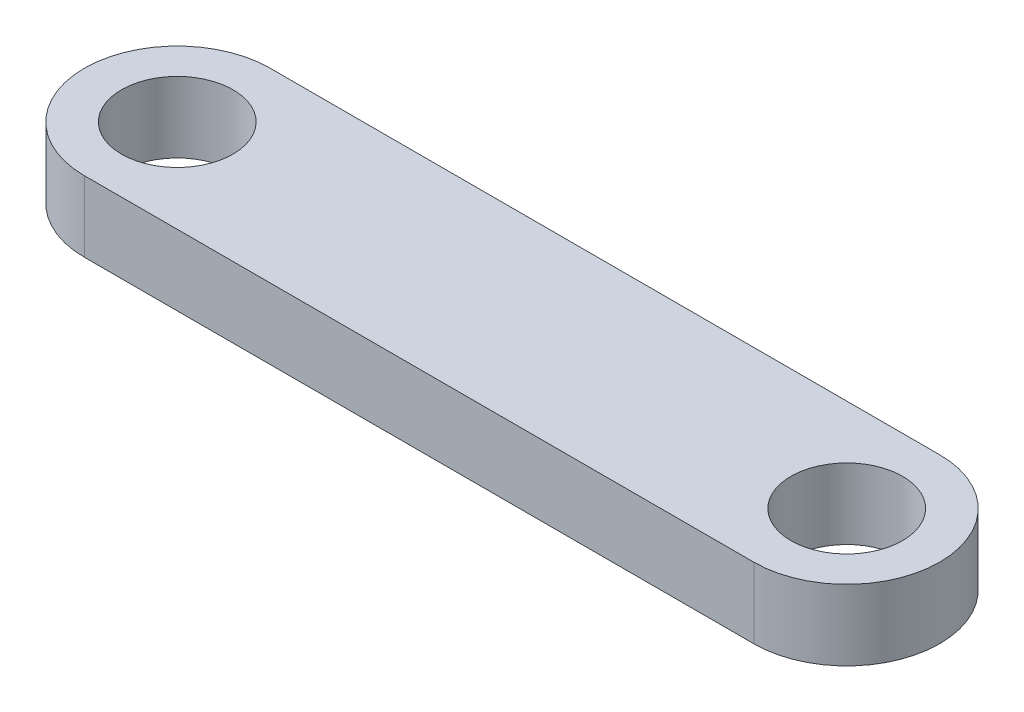
SolidWorks part; units mm, degrees
ref_plane "Front Plane" through (0, 0, 0) normal (0, 0, 1) x (1, 0, 0)
ref_plane "Top Plane" through (0, 0, 0) normal (0, 1, 0) x (1, 0, 0)
ref_plane "Right Plane" through (0, 0, 0) normal (1, 0, 0) x (0, 0, -1)
sketch "Sketch1" plane through (0, 0, 0) normal (0, 1, 0) x (1, 0, 0)
  line L0 (9, 0) -> (-9, 0) construction
  line L1 (9, -2.5) -> (-9, -2.5)
  line L2 (9, 2.5) -> (-9, 2.5)
  arc A0 (9, -2.5) -> (9, 2.5) centre (9, 0) ccw
  arc A1 (-9, 2.5) -> (-9, -2.5) centre (-9, 0) ccw
  point P2 (0, 0)
  dimension "D1" = 18
  dimension "D2" = 5
extrude "Boss-Extrude1" add sketch "Sketch1" along normal blind 1.9
sketch "Sketch2" plane through (0, 1.9, 0) normal (0, 1, 0) x (1, 0, 0)
  circle A0 centre (9, 0) radius 1.5
  circle A1 centre (-9, 0) radius 1.5
  dimension "D1" = 3
  dimension "D2" = 3
extrude "Cut-Extrude1" cut sketch "Sketch2" against normal through all
